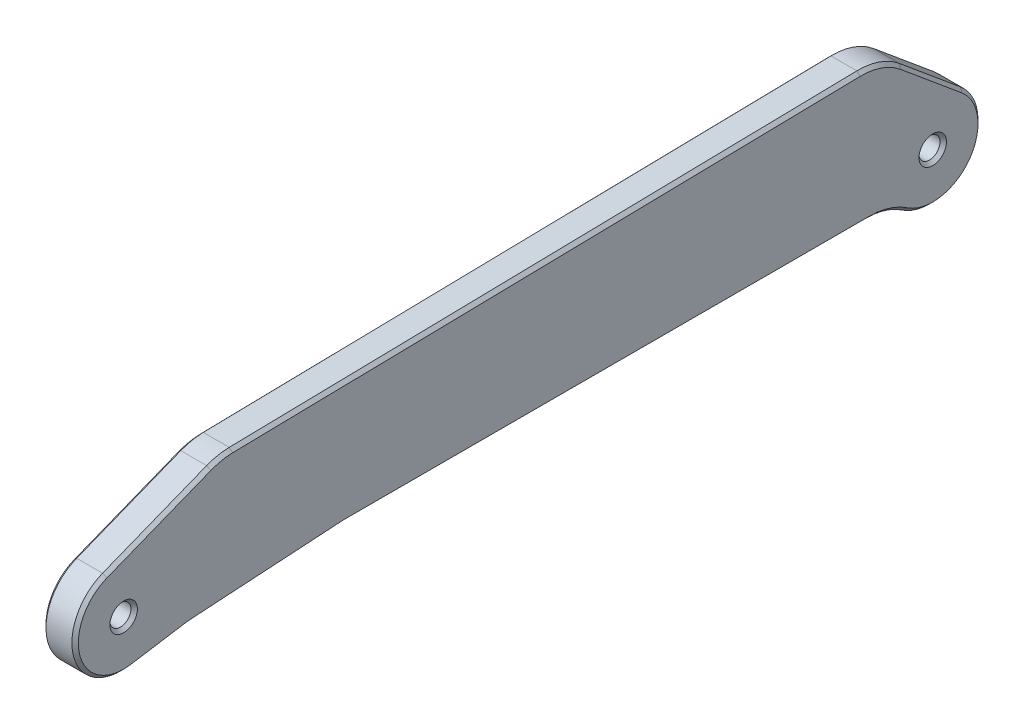
SolidWorks part; units mm, degrees
ref_plane "前视基准面" through (0, 0, 0) normal (0, 0, 1) x (1, 0, 0)
ref_plane "上视基准面" through (0, 0, 0) normal (0, 1, 0) x (1, 0, 0)
ref_plane "右视基准面" through (0, 0, 0) normal (1, 0, 0) x (0, 0, -1)
ref_plane "基准面1" through (-2.5, 0, 0) normal (-1, 0, 0) x (0, -1, 0)
sketch "草图1" plane through (-2.5, 0, 0) normal (-1, 0, 0) x (0, -1, 0)
  line L0 (-8.2599, 32.5452) -> (-6.9919, 97.5328)
  line L1 (-2.9926, 97.4548) -> (-4.2607, 32.4672)
  line L2 (-13.6153, 4.6348) -> (-5.7646, -4.7978)
  line L3 (4.5, 9.798) -> (4.5, 90.6878)
  line L4 (4.5195, 91.3116) -> (5.9701, 114.5219)
  line L5 (6.0754, 115.473) -> (7.4064, 123.8188)
  line L6 (-6.974, 127.7591) -> (-13.3359, 111.6787)
  line L7 (-14.0352, 108.195) -> (-15.9273, 11.227)
  circle A0 centre (0, 125) radius 1.625
  circle A1 centre (-8.5, 23.5) radius 1.575
  arc A2 (-6.9919, 97.5328) -> (-2.9926, 97.4548) centre (-4.9923, 97.4938) cw
  arc A3 (-4.2607, 32.4672) -> (-8.2599, 32.5452) centre (-6.2603, 32.5062) cw
  circle A4 centre (-5, 106.5) radius 1.575
  arc A5 (-15.9273, 11.227) -> (-13.6153, 4.6348) centre (-5.9292, 11.0319) ccw
  arc A6 (-5.7646, -4.7978) -> (6.2143, 4.1991) centre (0, 0) ccw
  arc A7 (6.2143, 4.1991) -> (4.5, 9.798) centre (14.5, 9.798) cw
  arc A8 (4.5, 90.6878) -> (4.5195, 91.3116) centre (14.5, 90.6878) cw
  arc A9 (5.9701, 114.5219) -> (6.0754, 115.473) centre (15.9506, 113.8981) cw
  arc A10 (7.4064, 123.8188) -> (-6.974, 127.7591) centre (0, 125) ccw
  arc A11 (-13.3359, 111.6787) -> (-14.0352, 108.195) centre (-4.0371, 107.9999) ccw
  circle A12 centre (0, 0) radius 1.625
  dimension "D4" = 3.25
  dimension "D5" = 3.15
  dimension "D6" = 2
  dimension "D7" = 2
  dimension "D12" = 7.5
  dimension "D14" = 3.25
  dimension "D15" = 3.15
  dimension "D16" = 10
  dimension "D18" = 7.5
  dimension "D19" = 10
  dimension "D1" = 200.467
  dimension "D2" = 17.2931
  dimension "D3" = 96.9864
  dimension "D8" = 64.9876
  dimension "D9" = 64.9876
  dimension "D10" = 80.8898
  dimension "D11" = 23.2103
  dimension "D13" = 8.3458
  dimension "D17" = 12.2723
extrude "凸台-拉伸1" add sketch "草图1" against normal blind 5
chamfer "倒角1" distance 0.5 angle 45 42 edges at (-2.5, 14.9812, 59.711) (-2.5, 13.8415, 109.9682) (-2.5, 10.1549, 119.7189) (-2.5, -1.982, 132.2334) (-2.5, -6.7409, 119.6459) (-2.5, -6.0114, 114.9987) (-2.5, -5.2448, 102.9168) (-2.5, -4.5049, 90.9998) (-2.5, -4.5, 50.2429) (-2.5, -4.9382, 6.8703) (-2.5, -4.5041, -5.9969) (-2.5, 9.69, -0.0815) (-2.5, 15.3657, 7.7225) (-2.5, 0, 123.375) (-2.5, 8.5, 21.925) (-2.5, 3.6267, 64.961) (-2.5, 4.9532, 99.4934) (-2.5, 7.6259, 65.039) (-2.5, 6.2993, 30.5066) (-2.5, 5, 104.925) (-2.5, 0, -1.625) (2.5, 9.69, -0.0815) (2.5, -4.5041, -5.9969) (2.5, -4.9382, 6.8703) (2.5, -4.5, 50.2429) (2.5, -4.5049, 90.9998) (2.5, -5.2448, 102.9168) (2.5, -6.0114, 114.9987) (2.5, -6.7409, 119.6459) (2.5, -1.982, 132.2334) (2.5, 10.1549, 119.7189) (2.5, 13.8415, 109.9682) (2.5, 14.9812, 59.711) (2.5, 15.3657, 7.7225) (2.5, 0, 123.375) (2.5, 8.5, 21.925) (2.5, 4.9532, 99.4934) (2.5, 3.6267, 64.961) (2.5, 6.2993, 30.5066) (2.5, 7.6259, 65.039) (2.5, 5, 104.925) (2.5, 0, -1.625)
sketch3d "3D草图1"
  line L1 (2.5, -0.1286, 115.0324) -> (2.5, -0.1286, 18.1008)
  line L2 (2.5, -0.1286, 115.0324) -> (2.5, -1.4474, 115.0324)
  line L3 (2.5, -1.4474, 115.0324) -> (2.5, -1.4474, 18.1008)
  line L4 (2.5, -0.1286, 18.1008) -> (2.5, -1.4474, 18.1008)
  line L5 (2.5, -0.1286, 115.0324) -> (2.5, -1.4474, 18.1008) construction
  line L6 (2.5, -1.4474, 115.0324) -> (2.5, -0.1286, 18.1008) construction
  point P0 (2.5, -0.788, 66.5666)
extrude "凸台-拉伸2" add sketch "3D草图1" along direction (-1, 0, 0) on the side against the normal blind 5
sketch3d "3D草图2"
  line L0 (2.5, 7.1319, 114.7785) -> (2.5, 10.2229, 96.8941)
  line L1 (2.5, 10.2229, 96.8941) -> (2.5, 12.159, 38.6628)
  line L2 (2.5, 12.159, 38.6628) -> (2.5, 12.8052, 19.2283)
  line L3 (2.5, 12.8052, 19.2283) -> (2.5, 3.4907, 14.5983)
  line L4 (2.5, 3.4907, 14.5983) -> (2.5, -2.222, 43.7762)
  line L5 (2.5, -2.222, 43.7762) -> (2.5, -0.2003, 109.5551)
  line L6 (2.5, -0.2003, 109.5551) -> (2.5, 7.1319, 114.7785)
extrude "凸台-拉伸3" add sketch "3D草图2" along direction (-1, 0, 0) on the side against the normal blind 5
